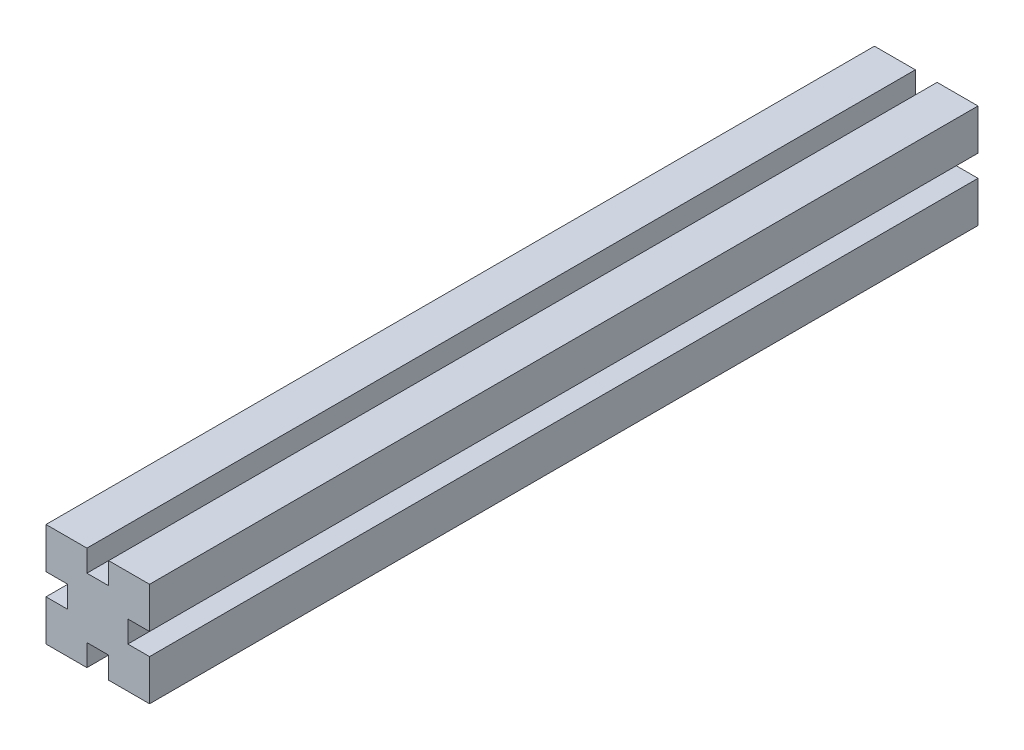
SolidWorks part; units mm, degrees
ref_plane "Front Plane" through (0, 0, 0) normal (0, 0, 1) x (1, 0, 0)
ref_plane "Top Plane" through (0, 0, 0) normal (0, 1, 0) x (1, 0, 0)
ref_plane "Right Plane" through (0, 0, 0) normal (1, 0, 0) x (0, 0, -1)
sketch "Sketch1" plane through (0, 0, 0) normal (0, 0, 1) x (1, 0, 0)
  line L0 (-19.05, -19.05) -> (-4, -19.05)
  line L1 (-4, -19.05) -> (-4, -11.05)
  line L2 (-4, -11.05) -> (4, -11.05)
  line L3 (4, -11.05) -> (4, -19.05)
  line L4 (4, -19.05) -> (19.05, -19.05)
  line L5 (19.05, -19.05) -> (19.05, -4)
  line L6 (19.05, -4) -> (11.05, -4)
  line L7 (11.05, -4) -> (11.05, 4)
  line L8 (11.05, 4) -> (19.05, 4)
  line L9 (19.05, 4) -> (19.05, 19.05)
  line L10 (19.05, 19.05) -> (4, 19.05)
  line L11 (4, 19.05) -> (4, 11.05)
  line L12 (4, 11.05) -> (-4, 11.05)
  line L13 (-4, 11.05) -> (-4, 19.05)
  line L14 (-4, 19.05) -> (-19.05, 19.05)
  line L15 (-19.05, 19.05) -> (-19.05, 4)
  line L16 (-19.05, 4) -> (-11.05, 4)
  line L17 (-11.05, 4) -> (-11.05, -4)
  line L18 (-11.05, -4) -> (-19.05, -4)
  line L19 (-19.05, -4) -> (-19.05, -19.05)
extrude "Profile" add sketch "Sketch1" along normal blind 304.8
equation "\"length\" = 304.8mm"
